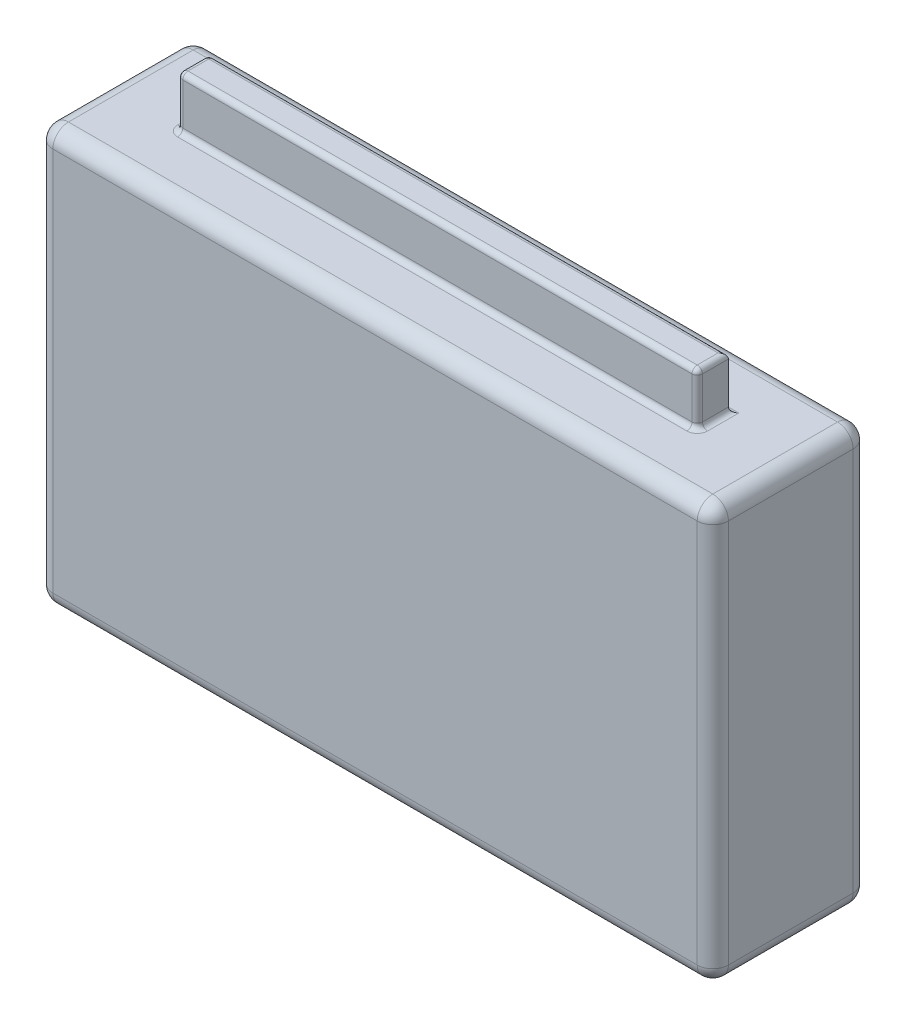
SolidWorks part; units mm, degrees
ref_plane "前视基准面" through (0, 0, 0) normal (0, 0, 1) x (1, 0, 0)
ref_plane "上视基准面" through (0, 0, 0) normal (0, 1, 0) x (1, 0, 0)
ref_plane "右视基准面" through (0, 0, 0) normal (1, 0, 0) x (0, 0, -1)
sketch "草图1" plane through (0, 0, 0) normal (0, 0, 1) x (1, 0, 0)
  line L1 (650, -400) -> (-650, -400)
  line L2 (650, -400) -> (650, 400)
  line L3 (650, 400) -> (-650, 400)
  line L4 (-650, -400) -> (-650, 400)
  line L5 (650, -400) -> (-650, 400) construction
  line L6 (650, 400) -> (-650, -400) construction
  point P0 (0, 0)
  dimension "D1" = 1300
  dimension "D2" = 800
extrude "凸台-拉伸1" add sketch "草图1" along normal blind 300
fillet "圆角1" radius 30 12 edges at (0, -400, 0) (-650, 0, 0) (-650, -400, 150) (0, -400, 300) (-650, 0, 300) (650, 0, 0) (650, -400, 150) (650, 0, 300) (650, 400, 150) (0, 400, 0) (-650, 400, 150) (0, 400, 300)
sketch "草图2" plane through (0, 400, 0) normal (0, 1, 0) x (1, 0, 0)
  line L0 (-754.9293, -150) -> (722.7224, -150) construction
  line L1 (-620, 0) -> (620, 0) construction
  line L2 (-650, -270) -> (-650, -30) construction
  line L3 (-500, -120) -> (500, -120)
  line L4 (-500, -120) -> (-500, -180)
  line L5 (-500, -180) -> (500, -180)
  line L6 (500, -120) -> (500, -180)
  dimension "D1" = 150
  dimension "D2" = 1000
  dimension "D3" = 150
  dimension "D4" = 60
  dimension "D5" = 30
extrude "凸台-拉伸2" add sketch "草图2" along normal blind 100
fillet "圆角2" radius 10 11 edges at (0, 400, 120) (500, 400, 150) (-500, 400, 150) (0, 500, 120) (500, 500, 150) (500, 450, 180) (-500, 450, 120) (-500, 500, 150) (-500, 450, 180) (0, 400, 180) (0, 500, 180)
